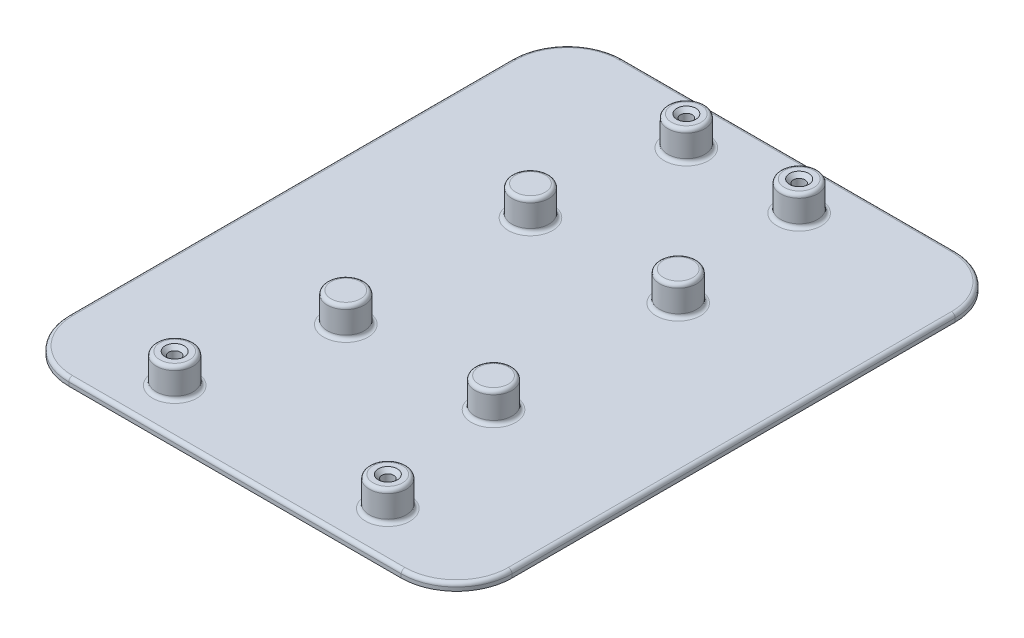
SolidWorks part; units mm, degrees
ref_plane "Front Plane" through (0, 0, 0) normal (0, 0, 1) x (1, 0, 0)
ref_plane "Top Plane" through (0, 0, 0) normal (0, 1, 0) x (1, 0, 0)
ref_plane "Right Plane" through (0, 0, 0) normal (1, 0, 0) x (0, 0, -1)
sketch "Sketch1" plane through (0, 0, 0) normal (0, 1, 0) x (1, 0, 0)
  line L1 (15, 0) -> (105, 0)
  line L2 (0, 15) -> (0, 135)
  line L3 (15, 150) -> (105, 150)
  line L4 (120, 15) -> (120, 135)
  arc A0 (15, 0) -> (0, 15) centre (15, 15) cw
  arc A1 (105, 0) -> (120, 15) centre (105, 15) ccw
  arc A2 (105, 150) -> (120, 135) centre (105, 135) cw
  arc A3 (0, 135) -> (15, 150) centre (15, 135) cw
  point P7 (0, 0)
  point P12 (120, 150)
  point P15 (0, 150)
  dimension "D3" = 15
  dimension "D1" = 150
  dimension "D2" = 120
extrude "Boss-Extrude1" add sketch "Sketch1" along normal blind 2
sketch "Sketch2" plane through (0, 2, 0) normal (0, 1, 0) x (1, 0, 0)
  line L0 (60, 0) -> (60, 150) construction
  line L1 (15, 0) -> (105, 0) construction
  line L2 (105, 150) -> (15, 150) construction
  line L3 (120, 75) -> (0, 75) construction
  line L4 (120, 15) -> (120, 135) construction
  line L5 (0, 135) -> (0, 15) construction
  circle A0 centre (44.725, 137.475) radius 1.5875
  circle A1 centre (75.275, 137.475) radius 1.5875
  circle A2 centre (88.85, 12.525) radius 1.5875
  circle A3 centre (31.15, 12.525) radius 1.5875
  circle A4 centre (44.725, 137.475) radius 5
  circle A5 centre (75.275, 137.475) radius 5
  circle A6 centre (31.15, 12.525) radius 5
  circle A7 centre (88.85, 12.525) radius 5
  circle A8 centre (40, 50) radius 5
  circle A9 centre (80, 50) radius 5
  circle A10 centre (40, 100) radius 5
  circle A11 centre (80, 100) radius 5
  dimension "D1" = 3.175
  dimension "D2" = 30.55
  dimension "D4" = 57.7
  dimension "D6" = 124.95
  dimension "D8" = 10
  dimension "D9" = 10
  dimension "D12" = 20
  dimension "D13" = 25
  dimension "D3" = 15.275
  dimension "D5" = 28.85
  dimension "D7" = 62.475
  dimension "D10" = 40
  dimension "D11" = 50
extrude "Boss-Extrude2" add sketch "Sketch2" along normal blind 8
fillet "Fillet1" radius 1 24 edges at (0, 2, -75) (4.3934, 2, -145.6066) (60, 2, -150) (115.6066, 2, -145.6066) (120, 2, -75) (115.6066, 2, -4.3934) (60, 2, 0) (75.275, 10, -132.475) (44.725, 10, -132.475) (88.85, 10, -7.525) (31.15, 10, -7.525) (4.3934, 2, -4.3934) (88.85, 2, -17.525) (31.15, 2, -17.525) (75.275, 2, -142.475) (44.725, 2, -142.475) (80, 10, -95) (40, 10, -45) (80, 10, -45) (40, 10, -95) (80, 2, -55) (40, 2, -105) (40, 2, -55) (80, 2, -105)
chamfer "Chamfer1" distance 1 angle 45 4 edges at (88.85, 10, -10.9375) (31.15, 10, -10.9375) (75.275, 10, -135.8875) (44.725, 10, -135.8875)
